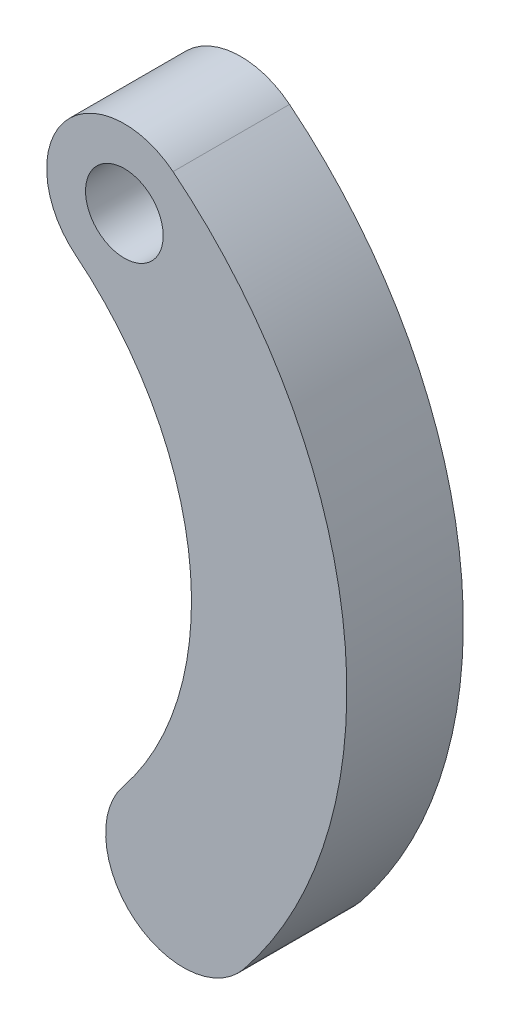
SolidWorks part; units mm, degrees
ref_plane "Front Plane" through (0, 0, 0) normal (0, 0, 1) x (1, 0, 0)
ref_plane "Top Plane" through (0, 0, 0) normal (0, 1, 0) x (1, 0, 0)
ref_plane "Right Plane" through (0, 0, 0) normal (1, 0, 0) x (0, 0, -1)
sketch "Sketch1" plane through (0, 0, 0) normal (0, 0, 1) x (1, 0, 0)
  circle A0 centre (0, 9.5) radius 1
  arc A1 (0, 9.5) -> (1.5186, -4.5604) centre (-6.2709, 1.7105) cw construction
  arc A2 (3.0765, -5.8145) -> (1.2542, 11.0579) centre (-6.2709, 1.7105) ccw
  arc A3 (-0.0393, -3.3062) -> (-1.2542, 7.9421) centre (-6.2709, 1.7105) ccw
  arc A4 (-0.0393, -3.3062) -> (3.0765, -5.8145) centre (1.5186, -4.5604) ccw
  arc A5 (1.2542, 11.0579) -> (-1.2542, 7.9421) centre (0, 9.5) ccw
  circle A6 centre (0, 0) radius 1.5 construction
  circle A7 centre (0, 9.5) radius 1 construction
  point P5 (3.6713, 2.7843)
  dimension "D1" = 4
  dimension "D3" = 10
  dimension "D2" = 90
extrude "Boss-Extrude1" add sketch "Sketch1" along normal blind 3
